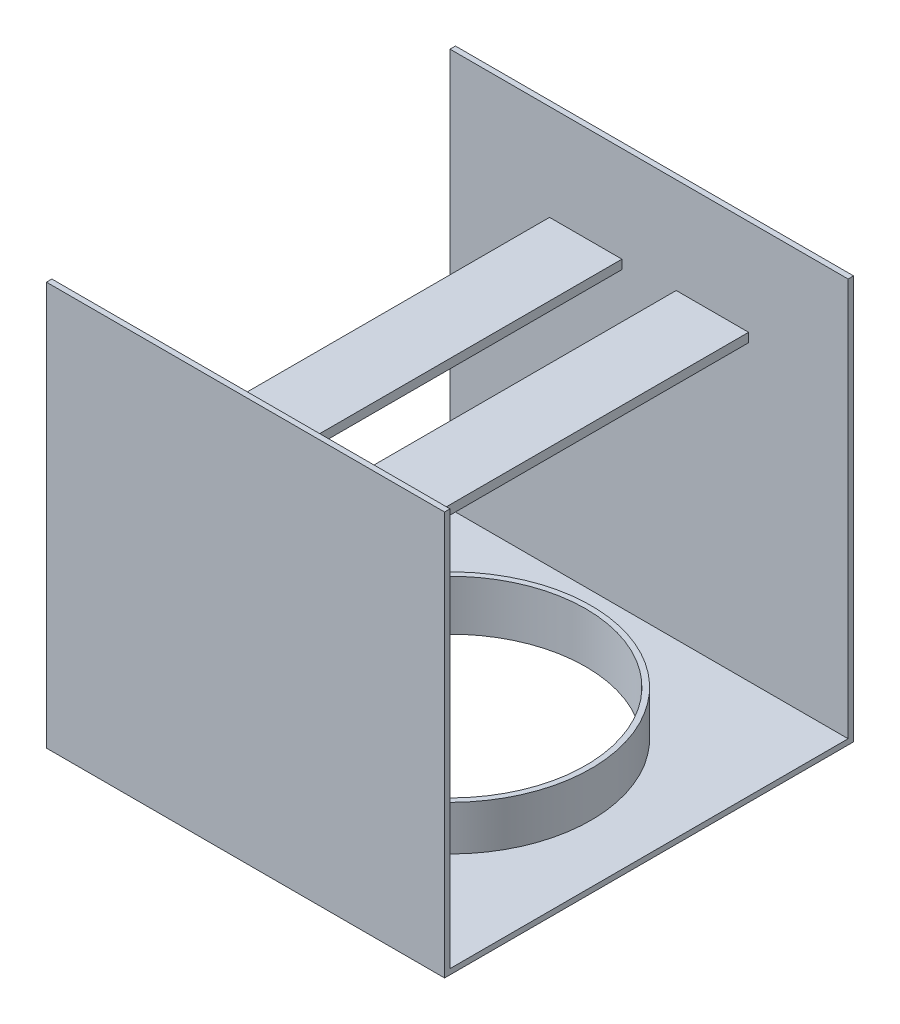
SolidWorks part; units mm, degrees
ref_plane "前视基准面" through (0, 0, 0) normal (0, 0, 1) x (1, 0, 0)
ref_plane "上视基准面" through (0, 0, 0) normal (0, 1, 0) x (1, 0, 0)
ref_plane "右视基准面" through (0, 0, 0) normal (1, 0, 0) x (0, 0, -1)
sketch "草图1" plane through (0, 0, 0) normal (0, 1, 0) x (1, 0, 0)
  line L1 (-110, 110) -> (110, 110)
  line L2 (-110, 110) -> (-110, -110)
  line L3 (-110, -110) -> (110, -110)
  line L4 (110, 110) -> (110, -110)
  line L5 (-110, 110) -> (110, -110) construction
  line L6 (-110, -110) -> (110, 110) construction
  point P0 (0, 0)
  dimension "D1" = 220
  dimension "D2" = 220
extrude "凸台-拉伸2" add sketch "草图1" along normal blind 220
sketch "草图3" plane through (0, 0, 0) normal (0, 1, 0) x (1, 0, 0)
  circle A0 centre (0, 0) radius 78
extrude "切除-拉伸1" cut sketch "草图3" along normal blind 240
shell "抽壳2" thickness 3
ref_plane "基准面4" through (78, 0, 0) normal (-1, 0, 0) x (0, 0, 1)
sketch "草图5" plane through (78, 0, 0) normal (-1, 0, 0) x (0, 0, 1)
  line L0 (-105.5527, 220) -> (-105.5527, 24.7156)
  line L1 (-113, 220) -> (113, 220) construction
  line L2 (-105.5527, 24.7156) -> (101.5696, 24.7156)
  line L3 (101.5696, 24.7156) -> (101.5696, 220)
  line L4 (101.5696, 220) -> (-105.5527, 220)
extrude "切除-拉伸3" cut sketch "草图5" along normal blind 180
ref_plane "基准面7" through (113, 0, 0) normal (1, 0, 0) x (0, 0, -1)
ref_plane "基准面8" through (-113, 0, 0) normal (-1, 0, 0) x (0, 0, 1)
sketch "草图12" plane through (113, 0, 0) normal (1, 0, 0) x (0, 0, -1)
  line L0 (-113, 220) -> (113, 220)
  line L1 (113, 220) -> (113, -3)
  line L2 (113, -3) -> (-113, -3)
  line L3 (-113, -3) -> (-113, 220)
extrude "切除-拉伸6" cut sketch "草图12" against normal blind 3
sketch "草图13" plane through (-113, 0, 0) normal (-1, 0, 0) x (0, 0, 1)
  line L0 (-113, 220) -> (-113, -3)
  line L1 (-113, -3) -> (113, -3)
  line L2 (113, -3) -> (113, 220)
  line L3 (113, 220) -> (-113, 220)
extrude "切除-拉伸7" cut sketch "草图13" against normal blind 3
sketch "草图16" plane through (0, 0, 0) normal (0, 0, 1) x (1, 0, 0)
  line L1 (-15, 167) -> (-55, 167)
  line L2 (-55, 167) -> (-55, 162)
  line L3 (-55, 162) -> (-15, 162)
  line L4 (-15, 162) -> (-15, 167)
  line L5 (15, 167) -> (15, 162)
  line L6 (15, 162) -> (55, 162)
  line L7 (55, 162) -> (55, 167)
  line L8 (55, 167) -> (15, 167)
  point P1 (0, 167)
  point P3 (15, 167)
  point P4 (-15, 167)
  point P5 (-55, 167)
  point P6 (55, 167)
  point P9 (-55, 162)
  dimension "D4" = 40
  dimension "D5" = 40
  dimension "D6" = 5
extrude "凸台-拉伸6" add sketch "草图16" against normal up to surface and the other way up to surface up to face at (0, 110, -110) other way up to face at (0, 110, 110)
ref_plane "基准面11" through (0, 0, 113) normal (0, 0, 1) x (1, 0, 0)
sketch "草图9" plane through (0, 0, 113) normal (0, 0, 1) x (1, 0, 0)
  line L0 (-110, -3) -> (110, -3) construction
  point P0 (0, 183.3163)
  dimension "D1" = 186.3163
